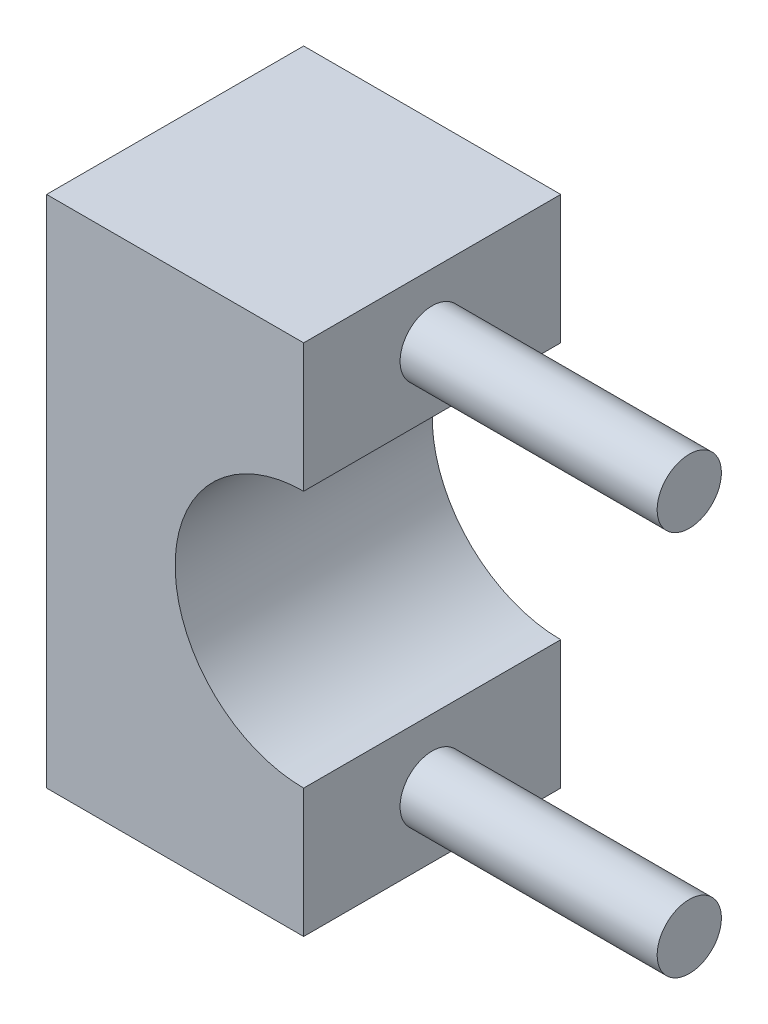
SolidWorks part; units mm, degrees
ref_plane "前视基准面" through (0, 0, 0) normal (0, 0, 1) x (1, 0, 0)
ref_plane "上视基准面" through (0, 0, 0) normal (0, 1, 0) x (1, 0, 0)
ref_plane "右视基准面" through (0, 0, 0) normal (1, 0, 0) x (0, 0, -1)
sketch "草图1" plane through (0, 0, 0) normal (0, 0, 1) x (1, 0, 0)
  line L5 (0, 20) -> (0, 10)
  line L6 (-20, 20) -> (0, 20)
  line L10 (-20, 20) -> (-20, -20)
  line L11 (-20, -20) -> (0, -20)
  line L13 (-20, 20) -> (-7.0711, 7.0711) construction
  line L14 (-20, -20) -> (-7.0711, -7.0711) construction
  line L15 (0, -10) -> (0, -20)
  arc A1 (0, 10) -> (0, -10) centre (0, 0) ccw
extrude "凸台-拉伸1" add sketch "草图1" along normal blind 20
sketch "草图3" plane through (0, 0, 0) normal (1, 0, 0) x (0, 0, -1)
  line L0 (-10, 20) -> (-10, -20) construction
  line L1 (-20, 20) -> (0, 20) construction
  line L2 (-20, -20) -> (0, -20) construction
  line L3 (-20, 15) -> (0, 15) construction
  line L4 (-20, 10) -> (-20, 20) construction
  line L5 (0, 10) -> (0, 20) construction
  line L6 (-20, -15) -> (0, -15) construction
  line L7 (-20, -20) -> (-20, -10) construction
  line L8 (0, -20) -> (0, -10) construction
  circle A0 centre (-10, 15) radius 2.5
  circle A1 centre (-10, -15) radius 2.5
extrude "凸台-拉伸2" add sketch "草图3" along normal blind 20
